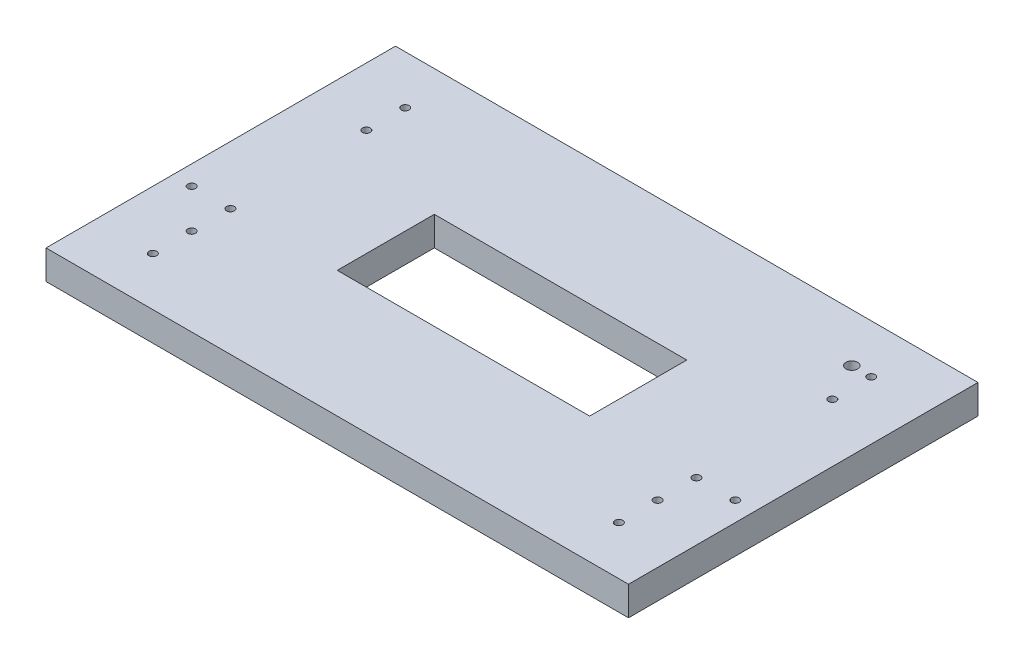
SolidWorks part; units mm, degrees
ref_plane "Alzado" through (0, 0, 0) normal (0, 0, 1) x (1, 0, 0)
ref_plane "Planta" through (0, 0, 0) normal (0, 1, 0) x (1, 0, 0)
ref_plane "Vista lateral" through (0, 0, 0) normal (1, 0, 0) x (0, 0, -1)
sketch "Croquis1" plane through (0, 0, 0) normal (0, 1, 0) x (1, 0, 0)
  line L1 (-150, -90) -> (150, -90)
  line L2 (-150, -90) -> (-150, 90)
  line L3 (-150, 90) -> (150, 90)
  line L4 (150, -90) -> (150, 90)
  line L5 (-150, -90) -> (150, 90) construction
  line L6 (-150, 90) -> (150, -90) construction
  point P0 (0, 0)
  dimension "D1" = 300
  dimension "D2" = 180
extrude "Saliente-Extruir1" add sketch "Croquis1" along normal blind 15
sketch "Croquis2" plane through (0, 15, 0) normal (0, 1, 0) x (1, 0, 0)
  line L0 (150, 90) -> (-150, 90) construction
  line L1 (-150, -90) -> (150, -90) construction
  line L2 (-150, 90) -> (-150, -90) construction
  line L3 (150, -90) -> (150, 90) construction
  circle A0 centre (-120, -45) radius 2
  circle A1 centre (-120, -65) radius 2
  circle A2 centre (120, -45) radius 2
  circle A3 centre (120, -65) radius 2
  circle A4 centre (-140, -25) radius 2
  circle A5 centre (-120, -25) radius 2
  circle A6 centre (120, -25) radius 2
  circle A7 centre (140, -25) radius 2
  circle A8 centre (-120, 65) radius 2
  circle A9 centre (-120, 45) radius 2
  circle A10 centre (120, 45) radius 2
  circle A11 centre (120, 65) radius 2
  dimension "D2" = 30
  dimension "D3" = 25
  dimension "D4" = 30
  dimension "D7" = 10
  dimension "D8" = 20
  dimension "D9" = 30
  dimension "D10" = 10
  dimension "D15" = 25
  dimension "D5" = 30
  dimension "D6" = 30
  dimension "D11" = 65
  dimension "D12" = 0
  dimension "D13" = 65
  dimension "D14" = 0
  dimension "D16" = 20
  dimension "D17" = 25
  dimension "D18" = 20
  dimension "D19" = 25
  dimension "D20" = 20
  dimension "D21" = 20
  dimension "D22" = 30
extrude "Cortar-Extruir1" cut sketch "Croquis2" against normal blind 10
sketch "Croquis3" plane through (0, 15, 0) normal (0, 1, 0) x (1, 0, 0)
  line L0 (150, -90) -> (150, 90) construction
  line L1 (-65, -25) -> (65, -25)
  line L2 (-65, -25) -> (-65, 25)
  line L3 (-65, 25) -> (65, 25)
  line L4 (65, -25) -> (65, 25)
  line L5 (-65, -25) -> (65, 25) construction
  line L6 (-65, 25) -> (65, -25) construction
  circle A0 centre (110, 65) radius 3
  point P0 (0, 0)
  dimension "D1" = 40
extrude "Cortar-Extruir2" cut sketch "Croquis3" against normal up to surface (15 mm away) up to face at (0, 0, 0)
sketch "Croquis4" plane through (0, 0, 0) normal (0, -1, 0) x (1, 0, 0)
  line L2 (150, -90) -> (-150, -90) construction
  line L3 (150, 90) -> (150, -90) construction
  circle A0 centre (140, -65) radius 2
  dimension "D1" = 25
  dimension "D2" = 10
extrude "Cortar-Extruir3" cut sketch "Croquis4" against normal blind 10
